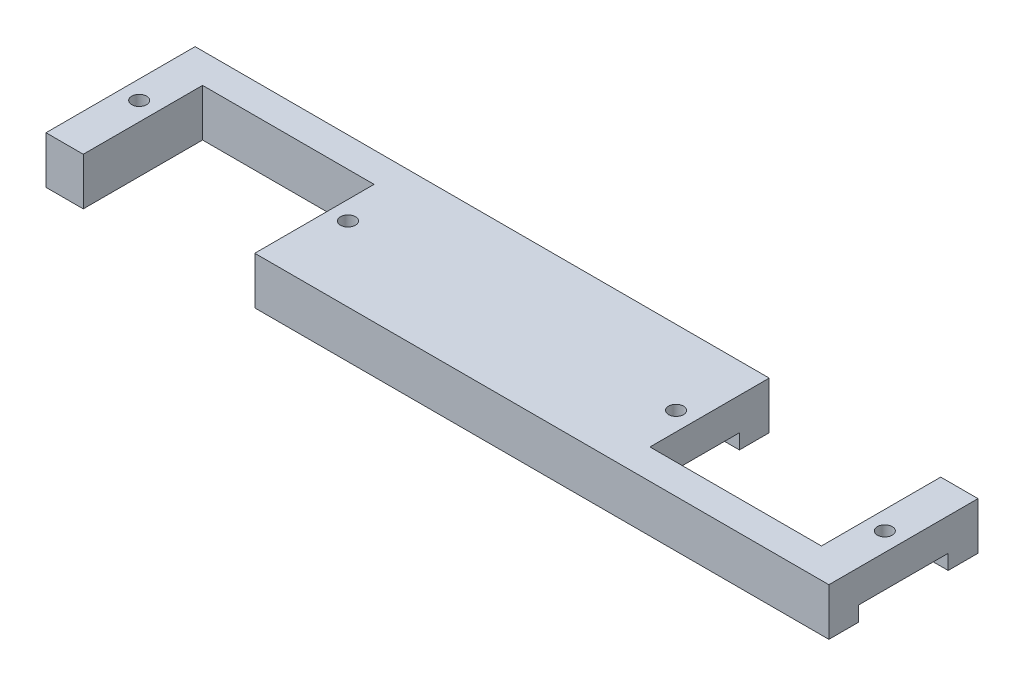
SolidWorks part; units mm, degrees
material "ABS"
ref_plane "Front" through (0, 0, 0) normal (0, 0, 1) x (1, 0, 0)
ref_plane "Top" through (0, 0, 0) normal (0, 1, 0) x (1, 0, 0)
ref_plane "Right" through (0, 0, 0) normal (1, 0, 0) x (0, 0, -1)
sketch "Sketch1" plane through (0, 0, 0) normal (0, 1, 0) x (1, 0, 0)
  line L1 (-52.5, 10) -> (52.5, 10)
  line L2 (-52.5, 10) -> (-52.5, -10)
  line L3 (-52.5, -10) -> (52.5, -10)
  line L4 (52.5, 10) -> (52.5, -10)
  line L5 (-52.5, 10) -> (52.5, -10) construction
  line L6 (-52.5, -10) -> (52.5, 10) construction
  point P0 (0, 0)
  dimension "D1" = 105
  dimension "D2" = 20
extrude "Boss-Extrude1" add sketch "Sketch1" along normal blind 6.35
sketch "Sketch3" plane through (0, 6.35, 0) normal (0, 1, 0) x (1, 0, 0)
  line L0 (-52.5, -10) -> (52.5, -10) construction
  line L1 (-47.5, -10) -> (-24.5, -10)
  line L2 (-47.5, -10) -> (-47.5, 6)
  line L3 (-47.5, 6) -> (-24.5, 6)
  line L4 (-24.5, -10) -> (-24.5, 6)
  line L5 (-52.5, 10) -> (-52.5, -10) construction
  line L6 (52.5, 10) -> (-52.5, 10) construction
  line L7 (52.5, -10) -> (52.5, 10) construction
  line L8 (24.5, 10) -> (47.5, 10)
  line L9 (24.5, 10) -> (24.5, -6)
  line L10 (24.5, -6) -> (47.5, -6)
  line L11 (47.5, 10) -> (47.5, -6)
  dimension "D1" = 23
  dimension "D2" = 5
  dimension "D3" = 4
  dimension "D4" = 5
  dimension "D5" = 4
extrude "Cut-Extrude1" cut sketch "Sketch3" against normal through all
sketch "Sketch4" plane through (0, 0, 0) normal (0, -1, 0) x (1, 0, 0)
  line L0 (24.5, -10) -> (24.5, 6) construction
  line L1 (24.5, 6) -> (19.5, 6)
  line L2 (24.5, 6) -> (24.5, -6)
  line L3 (24.5, -6) -> (19.5, -6)
  line L4 (19.5, 6) -> (19.5, -6)
  line L5 (47.5, 6) -> (47.5, -10) construction
  line L6 (47.5, 6) -> (52.5, 6)
  line L7 (47.5, 6) -> (47.5, -6)
  line L8 (47.5, -6) -> (52.5, -6)
  line L9 (52.5, 6) -> (52.5, -6)
  line L10 (24.5, -10) -> (52.5, 10) construction
  line L11 (24.5, 0) -> (47.5, 0) construction
  point P18 (38.5, 0)
  dimension "D1" = 5
  dimension "D2" = 12
extrude "Cut-Extrude2" cut sketch "Sketch4" against normal blind 2
hole_wizard "M2 Clearance Hole1" positions "Sketch7" profile "Sketch8" hole size "M2" standard "ANSI Metric" end condition through all
sketch "Sketch7" plane through (0, 6.35, 0) normal (0, 1, 0) x (1, 0, 0)
  line L0 (-52.5, 0) -> (52.5, 0) construction
  line L1 (-52.5, 10) -> (-52.5, -10) construction
  line L2 (52.5, -10) -> (52.5, 10) construction
  line L3 (24.5, 10) -> (24.5, -6) construction
  line L4 (47.5, -6) -> (47.5, 10) construction
  line L5 (-47.5, 6) -> (-47.5, -10) construction
  line L6 (-24.5, -10) -> (-24.5, 6) construction
  point P9 (-50, 0)
  point P11 (-22, 0)
  point P13 (22, 0)
  point P15 (50, 0)
  dimension "D1" = 2.5
  dimension "D2" = 2.5
  dimension "D3" = 2.5
  dimension "D4" = 2.5
sketch "Sketch8" plane through (50, 6.35, 0) normal (1, 0, 0) x (0, 0, 1)
  line L0 (0, 0) -> (0, 6.35)
  line L1 (0, 6.35) -> (1, 6.35)
  line L2 (1, 6.35) -> (1, 0)
  line L5 (1, 0) -> (0, 0)
  line L11 (0, -6.35) -> (0, 107.95) construction
  dimension "Thru Hole Dia." = 2
  dimension "Thru Hole Depth" = 6.35
